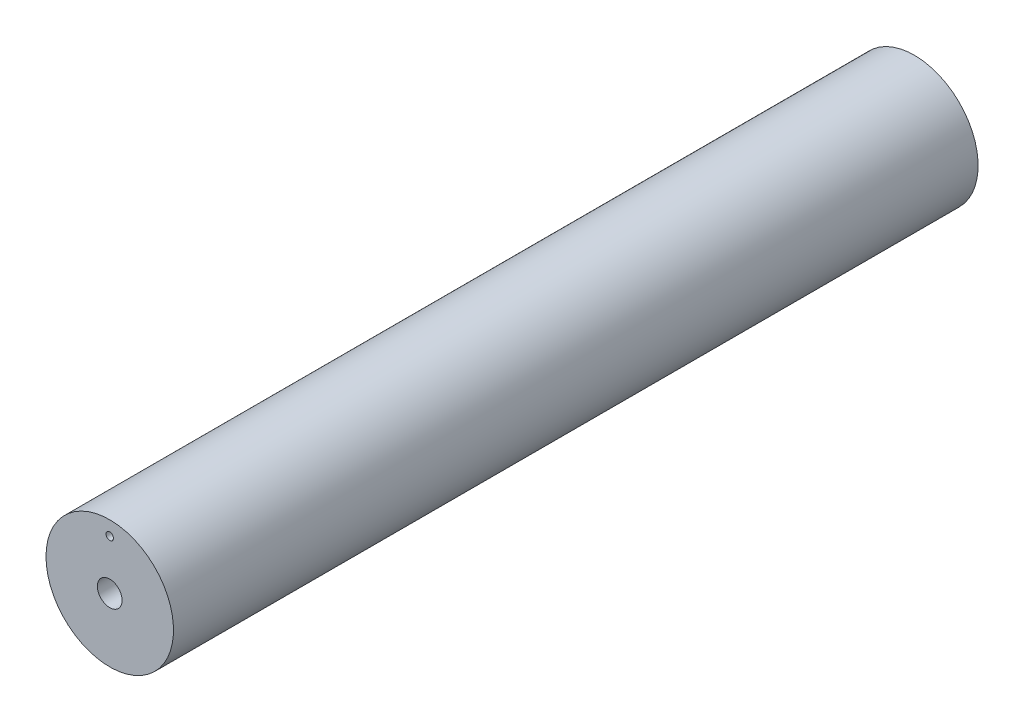
SolidWorks part; units mm, degrees
material "Plain Carbon Steel"
ref_plane "Front Plane" through (0, 0, 0) normal (0, 0, 1) x (1, 0, 0)
ref_plane "Top Plane" through (0, 0, 0) normal (0, 1, 0) x (1, 0, 0)
ref_plane "Right Plane" through (0, 0, 0) normal (1, 0, 0) x (0, 0, -1)
sketch "Sketch1" plane through (0, 0, 0) normal (0, 1, 0) x (1, 0, 0)
  line L0 (0, 325) -> (-25.75, 325)
  line L1 (-25.75, 325) -> (-25.75, 0)
  line L2 (-25.75, 0) -> (-5, 0)
  line L3 (-5, 0) -> (-5, 25)
  line L4 (-5, 25) -> (0, 25)
  line L5 (0, 25) -> (0, 325)
  line L6 (0, 14.8342) -> (0, -61.684) construction
  dimension "D1" = 51.5
  dimension "D2" = 10
  dimension "D3" = 25
  dimension "D4" = 325
revolve "Revolve1" add sketch "Sketch1" angle 360 about L6
sketch "Sketch2" plane through (0, 0, 0) normal (0, 1, 0) x (1, 0, 0)
  line L0 (25.75, 325) -> (-25.75, 325) construction
  circle A0 centre (0, 307.5) radius 5
  dimension "D1" = 10
  dimension "D2" = 17.5
extrude "Cut-Extrude1" cut sketch "Sketch2" against normal through all
sketch "Sketch3" plane through (0, 0, 0) normal (0, 0, 1) x (1, 0, 0)
  circle A0 centre (0, 20) radius 1.5
  circle A1 centre (0, 0) radius 25.75 construction
  dimension "D1" = 3
  dimension "D2" = 20
extrude "Cut-Extrude2" cut sketch "Sketch3" against normal blind 10
